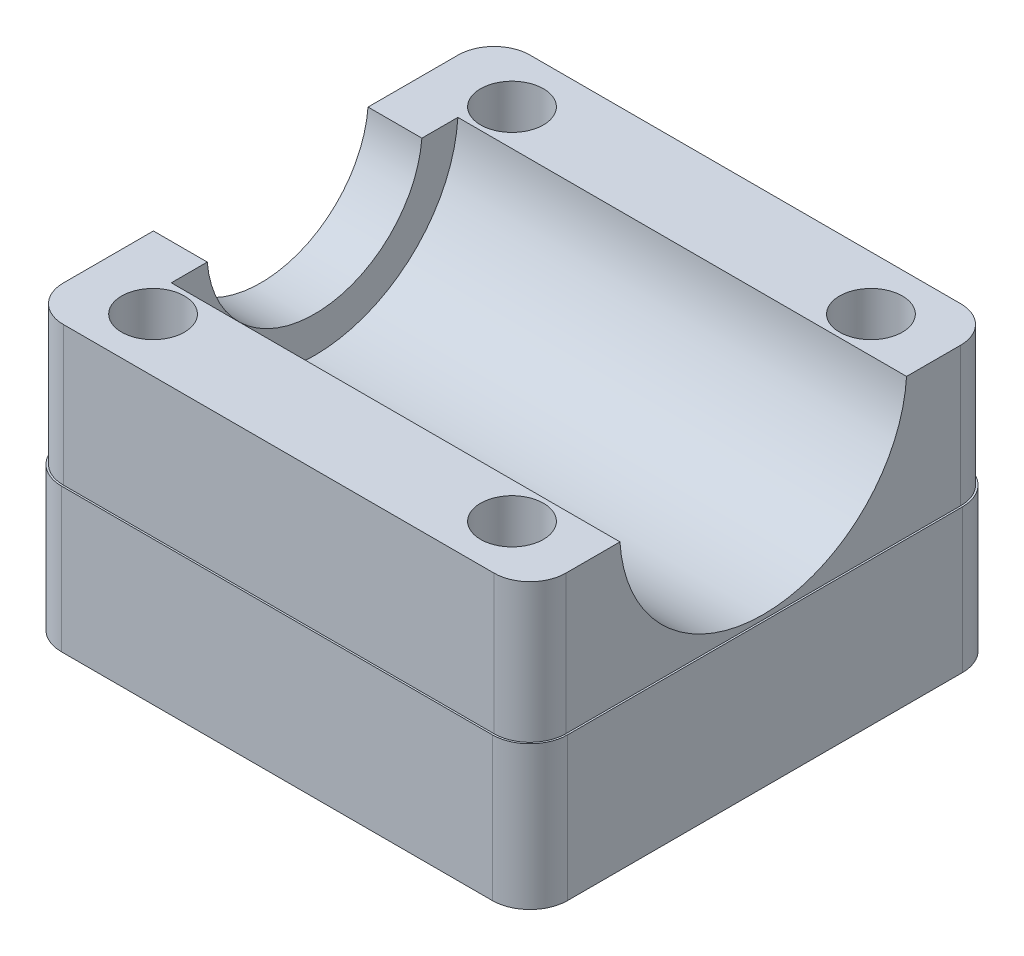
SolidWorks part; units mm, degrees
ref_plane "Front Plane" through (0, 0, 0) normal (0, 0, 1) x (1, 0, 0)
ref_plane "Top Plane" through (0, 0, 0) normal (0, 1, 0) x (1, 0, 0)
ref_plane "Right Plane" through (0, 0, 0) normal (1, 0, 0) x (0, 0, -1)
sketch "Sketch1" plane through (0, 0, 0) normal (1, 0, 0) x (0, 0, -1)
  line L1 (-13, -16.25) -> (13, -16.25)
  line L2 (-13, -16.25) -> (-13, 16.25)
  line L3 (-13, 16.25) -> (13, 16.25)
  line L4 (13, -16.25) -> (13, 16.25)
  line L5 (-13, -16.25) -> (13, 16.25) construction
  line L6 (-13, 16.25) -> (13, -16.25) construction
  circle A0 centre (0, 0) radius 8
  dimension "D1" = 16
  dimension "D2" = 32.5
  dimension "D3" = 26
extrude "Boss-Extrude1" add sketch "Sketch1" along normal mid plane 28
sketch "Sketch2" plane through (0, 16.25, 0) normal (0, 1, 0) x (1, 0, 0)
  line L1 (10, -10) -> (-10, -10) construction
  line L2 (10, -10) -> (10, 10) construction
  line L3 (10, 10) -> (-10, 10) construction
  line L4 (-10, -10) -> (-10, 10) construction
  line L5 (10, -10) -> (-10, 10) construction
  line L6 (10, 10) -> (-10, -10) construction
  circle A0 centre (-10, 10) radius 1.75
  circle A1 centre (10, 10) radius 1.75
  circle A2 centre (10, -10) radius 1.75
  circle A3 centre (-10, -10) radius 1.75
  point P0 (0, 0)
  dimension "D3" = 3.5
  dimension "D1" = 20
  dimension "D2" = 20
extrude "Cut-Extrude1" cut sketch "Sketch2" against normal blind 72
sketch "Sketch3" plane through (-14, 0, 0) normal (-1, 0, 0) x (0, 0, 1)
  line L0 (0, 0) -> (-13, 0) construction
  line L1 (-13, -16.25) -> (-13, 16.25) construction
  line L2 (0, 0) -> (13, 0) construction
  line L3 (13, 16.25) -> (13, -16.25) construction
  line L4 (-13, -0.5) -> (13, -0.5) construction
  line L5 (13, 0.5) -> (-13, 0.5) construction
  line L9 (-13, -0.5) -> (-13, 16.25)
  line L10 (-13, 16.25) -> (13, 16.25)
  line L11 (13, 16.25) -> (13, -0.5)
  line L12 (13, -0.5) -> (-13, -0.5)
  dimension "D1" = 0.5
  dimension "D2" = 0.5
extrude "Cut-Extrude3" cut sketch "Sketch3" against normal blind 32
fillet "Fillet2" radius 2 4 edges at (14, -8.375, -13) (-14, -8.375, -13) (14, -8.375, 13) (-14, -8.375, 13)
sketch "Sketch4" plane through (-14, 0, 0) normal (1, 0, 0) x (0, 0, -1)
  line L0 (-7.9844, -0.5) -> (-5.9791, -0.5)
  line L1 (5.9791, -0.5) -> (7.9844, -0.5)
  arc A0 (-7.9844, -0.5) -> (7.9844, -0.5) centre (0, 0) ccw
  arc A1 (-5.9791, -0.5) -> (5.9791, -0.5) centre (0, 0) ccw
  dimension "D1" = 12
extrude "Boss-Extrude2" add sketch "Sketch4" along normal blind 3
sketch "Sketch5" plane through (0, -16.25, 0) normal (0, -1, 0) x (1, 0, 0)
  line L1 (-6.5936, 10) -> (-8.2968, 12.95)
  line L2 (-8.2968, 12.95) -> (-11.7032, 12.95)
  line L3 (-11.7032, 12.95) -> (-13.4064, 10)
  line L4 (-13.4064, 10) -> (-11.7032, 7.05)
  line L5 (-11.7032, 7.05) -> (-8.2968, 7.05)
  line L6 (-8.2968, 7.05) -> (-6.5936, 10)
  line L8 (8.4123, 6.85) -> (6.8246, 10)
  line L9 (11.5877, 6.85) -> (8.4123, 6.85)
  line L10 (13.1754, 10) -> (11.5877, 6.85)
  line L11 (11.5877, 12.75) -> (13.1754, 10)
  line L12 (8.4123, 12.75) -> (11.5877, 12.75)
  line L13 (6.8246, 10) -> (8.4123, 12.75)
  line L52 (6.8246, -10) -> (8.4123, -12.75)
  line L53 (8.4123, -12.75) -> (11.5877, -12.75)
  line L54 (11.5877, -12.75) -> (13.1754, -10)
  line L55 (13.1754, -10) -> (11.5877, -7.25)
  line L56 (11.5877, -7.25) -> (8.4123, -7.25)
  line L57 (8.4123, -7.25) -> (6.8246, -10)
  line L58 (-8.4123, -7.25) -> (-6.8246, -10)
  line L59 (-11.5877, -7.25) -> (-8.4123, -7.25)
  line L60 (-13.1754, -10) -> (-11.5877, -7.25)
  line L61 (-11.5877, -12.75) -> (-13.1754, -10)
  line L62 (-8.4123, -12.75) -> (-11.5877, -12.75)
  line L63 (-6.8246, -10) -> (-8.4123, -12.75)
  circle A0 centre (-10, 10) radius 2.95 construction
  circle A1 centre (10, 10) radius 2.75 construction
  circle A2 centre (-10, 10) radius 2.75 construction
  circle A3 centre (10, 10) radius 2.75 construction
  circle A4 centre (-10, 10) radius 2.75 construction
  circle A5 centre (10, 10) radius 2.75 construction
  circle A6 centre (-10, 10) radius 2.75 construction
  circle A7 centre (10, 10) radius 2.75 construction
  circle A8 centre (10, -10) radius 2.75 construction
  circle A9 centre (-10, -10) radius 2.75 construction
  circle A10 centre (10, -10) radius 2.75 construction
  circle A11 centre (-10, -10) radius 2.75 construction
  circle A12 centre (10, -10) radius 2.75 construction
  circle A13 centre (-10, -10) radius 2.75 construction
  circle A14 centre (10, -10) radius 2.75 construction
  circle A15 centre (-10, -10) radius 2.75 construction
  dimension "D1" = 5.9
  dimension "D2" = 5.9
  dimension "D3" = 5.5
extrude "Cut-Extrude4" cut sketch "Sketch5" against normal blind 3
sketch "Sketch6" plane through (0, -16.25, 0) normal (0, -1, 0) x (1, 0, 0)
  line L30 (-12, -15.5) -> (12, -15.5)
  line L31 (12, 15.5) -> (-12, 15.5)
  line L32 (16.5, -11) -> (16.5, 11)
  line L33 (-16.5, 11) -> (-16.5, -11)
  line L34 (-12, -15.5) -> (12, -15.5)
  line L35 (12, 15.5) -> (-12, 15.5)
  line L36 (16.5, -11) -> (16.5, 11)
  line L37 (-16.5, 11) -> (-16.5, -11)
  line L58 (-12, -13) -> (12, -13)
  line L59 (14, -11) -> (14, 11)
  line L60 (12, 13) -> (-12, 13)
  line L61 (-14, 11) -> (-14, -11)
  line L62 (-12, -13) -> (12, -13)
  line L63 (14, -11) -> (14, 11)
  line L64 (12, 13) -> (-12, 13)
  line L65 (-14, 11) -> (-14, -11)
  arc A4 (16.5, 11) -> (12, 15.5) centre (12, 11) ccw
  arc A5 (16.5, 11) -> (12, 15.5) centre (12, 11) ccw
  arc A6 (-12, 15.5) -> (-16.5, 11) centre (-12, 11) ccw
  arc A7 (-12, 15.5) -> (-16.5, 11) centre (-12, 11) ccw
  arc A8 (12, -15.5) -> (16.5, -11) centre (12, -11) ccw
  arc A9 (12, -15.5) -> (16.5, -11) centre (12, -11) ccw
  arc A10 (-16.5, -11) -> (-12, -15.5) centre (-12, -11) ccw
  arc A11 (-16.5, -11) -> (-12, -15.5) centre (-12, -11) ccw
  arc A38 (-14, -11) -> (-12, -13) centre (-12, -11) ccw
  arc A39 (12, -13) -> (14, -11) centre (12, -11) ccw
  arc A40 (14, 11) -> (12, 13) centre (12, 11) ccw
  arc A41 (-12, 13) -> (-14, 11) centre (-12, 11) ccw
  arc A42 (-14, -11) -> (-12, -13) centre (-12, -11) ccw
  arc A43 (12, -13) -> (14, -11) centre (12, -11) ccw
  arc A44 (14, 11) -> (12, 13) centre (12, 11) ccw
  arc A45 (-12, 13) -> (-14, 11) centre (-12, 11) ccw
  dimension "D1" = 2.5
  dimension "D2" = 0
extrude "Boss-Extrude3" add sketch "Sketch6" against normal blind 8
sketch "Sketch7" plane through (0, -16.25, 0) normal (0, -1, 0) x (1, 0, 0)
  line L1 (-6.5936, 10) -> (-8.2968, 12.95)
  line L2 (-8.2968, 12.95) -> (-11.7032, 12.95)
  line L3 (-11.7032, 12.95) -> (-13.4064, 10)
  line L4 (-13.4064, 10) -> (-11.7032, 7.05)
  line L5 (-11.7032, 7.05) -> (-8.2968, 7.05)
  line L6 (-8.2968, 7.05) -> (-6.5936, 10)
  line L7 (13.4064, 10) -> (11.7032, 12.95)
  line L8 (11.7032, 12.95) -> (8.2968, 12.95)
  line L9 (8.2968, 12.95) -> (6.5936, 10)
  line L10 (6.5936, 10) -> (8.2968, 7.05)
  line L11 (8.2968, 7.05) -> (11.7032, 7.05)
  line L12 (11.7032, 7.05) -> (13.4064, 10)
  line L13 (-6.5936, -10) -> (-8.2968, -7.05)
  line L14 (-8.2968, -7.05) -> (-11.7032, -7.05)
  line L15 (-11.7032, -7.05) -> (-13.4064, -10)
  line L16 (-13.4064, -10) -> (-11.7032, -12.95)
  line L17 (-11.7032, -12.95) -> (-8.2968, -12.95)
  line L18 (-8.2968, -12.95) -> (-6.5936, -10)
  line L19 (13.4064, -10) -> (11.7032, -7.05)
  line L20 (11.7032, -7.05) -> (8.2968, -7.05)
  line L21 (8.2968, -7.05) -> (6.5936, -10)
  line L22 (6.5936, -10) -> (8.2968, -12.95)
  line L23 (8.2968, -12.95) -> (11.7032, -12.95)
  line L24 (11.7032, -12.95) -> (13.4064, -10)
  circle A0 centre (-10, 10) radius 2.95 construction
  circle A1 centre (10, 10) radius 2.95 construction
  circle A2 centre (-10, -10) radius 2.95 construction
  circle A3 centre (10, -10) radius 2.95 construction
  dimension "D1" = 5.9
  dimension "D2" = 5.9
  dimension "D3" = 5.9
  dimension "D4" = 5.9
extrude "Cut-Extrude5" cut sketch "Sketch7" against normal up to surface (3 mm away) up to face at (-10, -13.25, 10)
sketch "Sketch8" plane through (0, -8.25, 0) normal (0, 1, 0) x (1, 0, 0)
  line L20 (-14.1, 11) -> (-14.1, -11)
  line L21 (-12, -13.1) -> (12, -13.1)
  line L22 (14.1, -11) -> (14.1, 11)
  line L23 (12, 13.1) -> (-12, 13.1)
  line L24 (-14.1, 11) -> (-14.1, -11)
  line L25 (-12, -13.1) -> (12, -13.1)
  line L26 (14.1, -11) -> (14.1, 11)
  line L27 (12, 13.1) -> (-12, 13.1)
  line L32 (-12, -15.7) -> (12, -15.7)
  line L33 (16.7, -11) -> (16.7, 11)
  line L34 (12, 15.7) -> (-12, 15.7)
  line L35 (-16.7, 11) -> (-16.7, -11)
  line L36 (-12, -15.7) -> (12, -15.7)
  line L37 (16.7, -11) -> (16.7, 11)
  line L38 (12, 15.7) -> (-12, 15.7)
  line L39 (-16.7, 11) -> (-16.7, -11)
  arc A24 (-14.1, -11) -> (-12, -13.1) centre (-12, -11) ccw
  arc A25 (12, -13.1) -> (14.1, -11) centre (12, -11) ccw
  arc A26 (14.1, 11) -> (12, 13.1) centre (12, 11) ccw
  arc A27 (-12, 13.1) -> (-14.1, 11) centre (-12, 11) ccw
  arc A28 (-14.1, -11) -> (-12, -13.1) centre (-12, -11) ccw
  arc A29 (12, -13.1) -> (14.1, -11) centre (12, -11) ccw
  arc A30 (14.1, 11) -> (12, 13.1) centre (12, 11) ccw
  arc A31 (-12, 13.1) -> (-14.1, 11) centre (-12, 11) ccw
  arc A36 (-16.7, -11) -> (-12, -15.7) centre (-12, -11) ccw
  arc A37 (12, -15.7) -> (16.7, -11) centre (12, -11) ccw
  arc A38 (16.7, 11) -> (12, 15.7) centre (12, 11) ccw
  arc A39 (-12, 15.7) -> (-16.7, 11) centre (-12, 11) ccw
  arc A40 (-16.7, -11) -> (-12, -15.7) centre (-12, -11) ccw
  arc A41 (12, -15.7) -> (16.7, -11) centre (12, -11) ccw
  arc A42 (16.7, 11) -> (12, 15.7) centre (12, 11) ccw
  arc A43 (-12, 15.7) -> (-16.7, 11) centre (-12, 11) ccw
  dimension "D1" = 0.1
  dimension "D2" = 0.2
extrude "Cut-Extrude6" cut sketch "Sketch8" against normal through all
